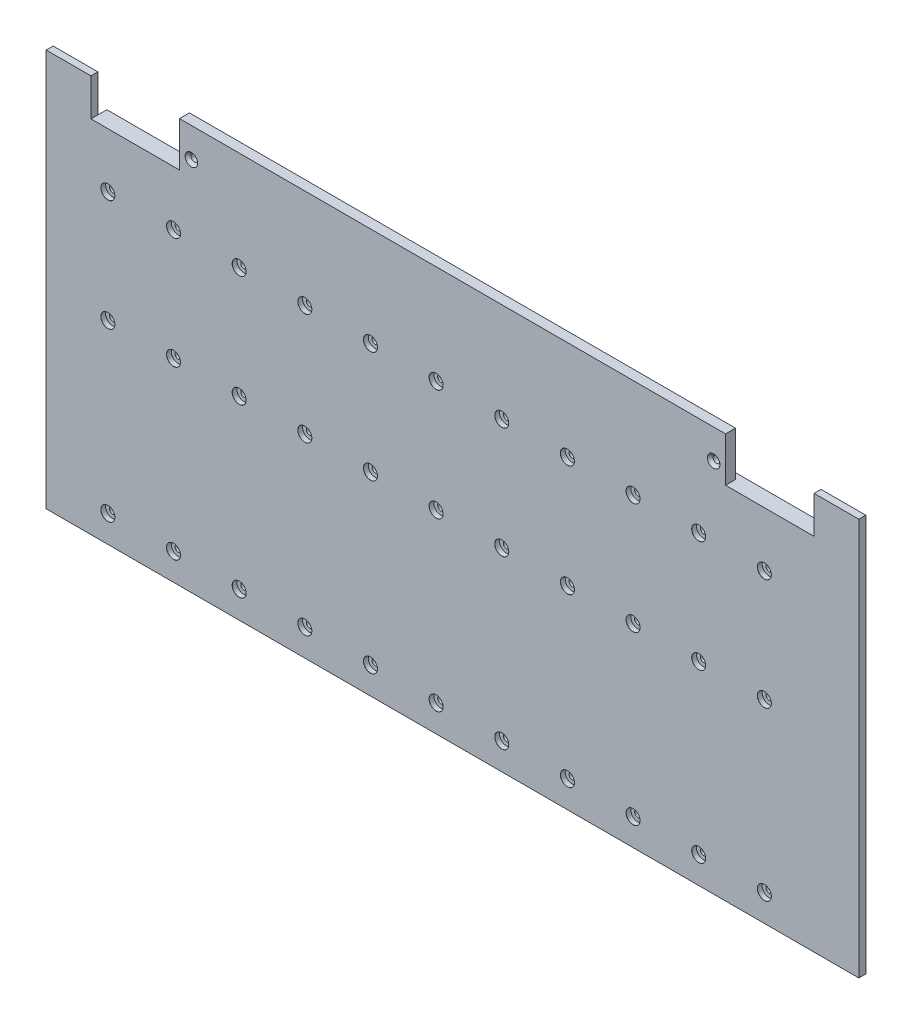
SolidWorks part; units mm, degrees
ref_plane "Plan de face" through (0, 0, 0) normal (0, 0, 1) x (1, 0, 0)
ref_plane "Plan de dessus" through (0, 0, 0) normal (0, 1, 0) x (1, 0, 0)
ref_plane "Plan de droite" through (0, 0, 0) normal (1, 0, 0) x (0, 0, -1)
sketch "Esquisse1" plane through (0, 0, 0) normal (0, 0, 1) x (1, 0, 0)
  line L1 (-204.25, -90.5) -> (204.25, -90.5)
  line L2 (-204.25, -90.5) -> (-204.25, 90.5)
  line L3 (-204.25, 90.5) -> (204.25, 90.5)
  line L4 (204.25, -90.5) -> (204.25, 90.5)
  line L5 (-204.25, -90.5) -> (204.25, 90.5) construction
  line L6 (-204.25, 90.5) -> (204.25, -90.5) construction
  point P0 (0, 0)
  dimension "D1" = 181
  dimension "D2" = 408.5
extrude "Boss.-Extru.1" add sketch "Esquisse1" along normal blind 8 contours L3 L4 L1 L2
hole_wizard "Chambrage pour vis à tête ronde bombée M31" positions "Esquisse2" profile "Esquisse3" counterbore size "M3" standard "Ansi Metric" end condition through all
sketch "Esquisse2" plane through (0, 0, 8) normal (0, 0, 1) x (1, 0, 0)
  point P0 (-173.25, 63)
  point P3 (-173.25, 7)
  point P6 (-173.25, -77)
sketch "Esquisse3" plane through (-173.25, 63, 8) normal (1, 0, 0) x (0, -1, 0)
  line L0 (0, 0) -> (0, 8)
  line L1 (0, 8) -> (1.6, 8)
  line L3 (1.6, 8) -> (1.6, 2.4)
  line L4 (3.5, 2.4) -> (1.6, 2.4)
  line L5 (3.5, 2.4) -> (3.5, 0.025)
  line L6 (3.5, 0.025) -> (3.525, 0)
  line L7 (3.525, 0) -> (0, 0)
  line L8 (-3.5, 0.025) -> (-3.525, 0) construction
  line L11 (0, -6.35) -> (0, 107.95) construction
  dimension "Diamètre du perçage jusqu'au prochain" = 3.2
  dimension "Profondeur du perçage jusqu'au prochain" = 8
  dimension "Diamètre du chambrage" = 7
  dimension "Profondeur du chambrage" = 2.4
  dimension "Diamètre du fraisage entrant" = 7.05
  dimension "Angle du fraisage entrant" = 90
pattern_linear "Répétition linéaire1" count 11 spacing 33 along (1, 0, 0) of "Chambrage pour vis à tête ronde bombée M31"
sketch "Esquisse6" plane through (0, 90.5, 0) normal (0, 1, 0) x (1, 0, 0)
  line L0 (-204.25, 0) -> (204.25, 0) construction
  line L1 (-204.25, 0) -> (-181.75, 0)
  line L2 (-204.25, 0) -> (-204.25, -4.5)
  line L3 (-204.25, -4.5) -> (-181.75, -4.5)
  line L4 (-181.75, 0) -> (-181.75, -4.5)
  line L6 (-204.25, -8) -> (204.25, -8) construction
  line L7 (0, -4.4) -> (0, 4.4) construction
  line L8 (181.75, 0) -> (181.75, -4.5)
  line L9 (204.25, -4.5) -> (181.75, -4.5)
  line L10 (204.25, 0) -> (204.25, -4.5)
  line L11 (204.25, 0) -> (181.75, 0)
  line L12 (-204.25, -8) -> (-204.25, 0) construction
  dimension "D2" = 3.5
  dimension "D3" = 22.5
extrude "Enlèv. mat.-Extru.1" cut sketch "Esquisse6" against normal up to next
sketch "Esquisse7" plane through (0, 0, 8) normal (0, 0, 1) x (1, 0, 0)
  line L1 (-204.25, 90.5) -> (-181.75, 90.5)
  line L2 (-204.25, 90.5) -> (-204.25, 109.225)
  line L3 (-204.25, 109.225) -> (-181.75, 109.225)
  line L4 (-181.75, 90.5) -> (-181.75, 109.225)
  dimension "D1" = 22.5
  dimension "D2" = 18.725
extrude "Boss.-Extru.2" add sketch "Esquisse7" against normal up to vertex
mirror "Symétrie1" about plane through (0, 0, 0) normal (1, 0, 0) of "Boss.-Extru.2"
sketch "Esquisse8" plane through (0, 0, 8) normal (0, 0, 1) x (1, 0, 0)
  line L0 (-181.75, 90.5) -> (181.75, 90.5) construction
  line L1 (-137.25, 90.5) -> (137.25, 90.5)
  line L2 (-137.25, 90.5) -> (-137.25, 112.875)
  line L3 (-137.25, 112.875) -> (137.25, 112.875)
  line L4 (137.25, 90.5) -> (137.25, 112.875)
  line L5 (-137.75, 91) -> (-137.75, 116.55) construction
  line L7 (124.75, 113.375) -> (137.75, 113.375) construction
  line L8 (137.75, 91) -> (137.75, 116.55) construction
  dimension "D1" = 0.5
  dimension "D2" = 0.5
  dimension "D3" = 0.5
extrude "Boss.-Extru.3" add sketch "Esquisse8" against normal blind 5
hole_wizard "Fraisage pour vis à tête fraisée M31" positions "Esquisse9" profile "Esquisse10" countersink size "M3" standard "Ansi Metric" end condition through all
sketch "Esquisse9" plane through (0, 0, 8) normal (0, 0, 1) x (1, 0, 0)
  point P0 (-131.25, 98)
  point P3 (131.25, 98)
sketch "Esquisse10" plane through (-131.25, 98, 8) normal (1, 0, 0) x (0, -1, 0)
  line L0 (0, 0) -> (0, 8)
  line L1 (0, 8) -> (1.7, 8)
  line L2 (1.7, 8) -> (1.7, 1.45)
  line L3 (1.7, 1.45) -> (3.15, 0)
  line L5 (3.15, 0) -> (0, 0)
  line L6 (-1.7, 1.45) -> (-3.15, 0) construction
  line L11 (0, -6.35) -> (0, 107.95) construction
  dimension "Diamètre du perçage jusqu'au prochain" = 3.4
  dimension "Profondeur du perçage jusqu'au prochain" = 8
  dimension "Diamètre du fraisage entrant" = 6.3
  dimension "Angle du fraisage entrant" = 90
